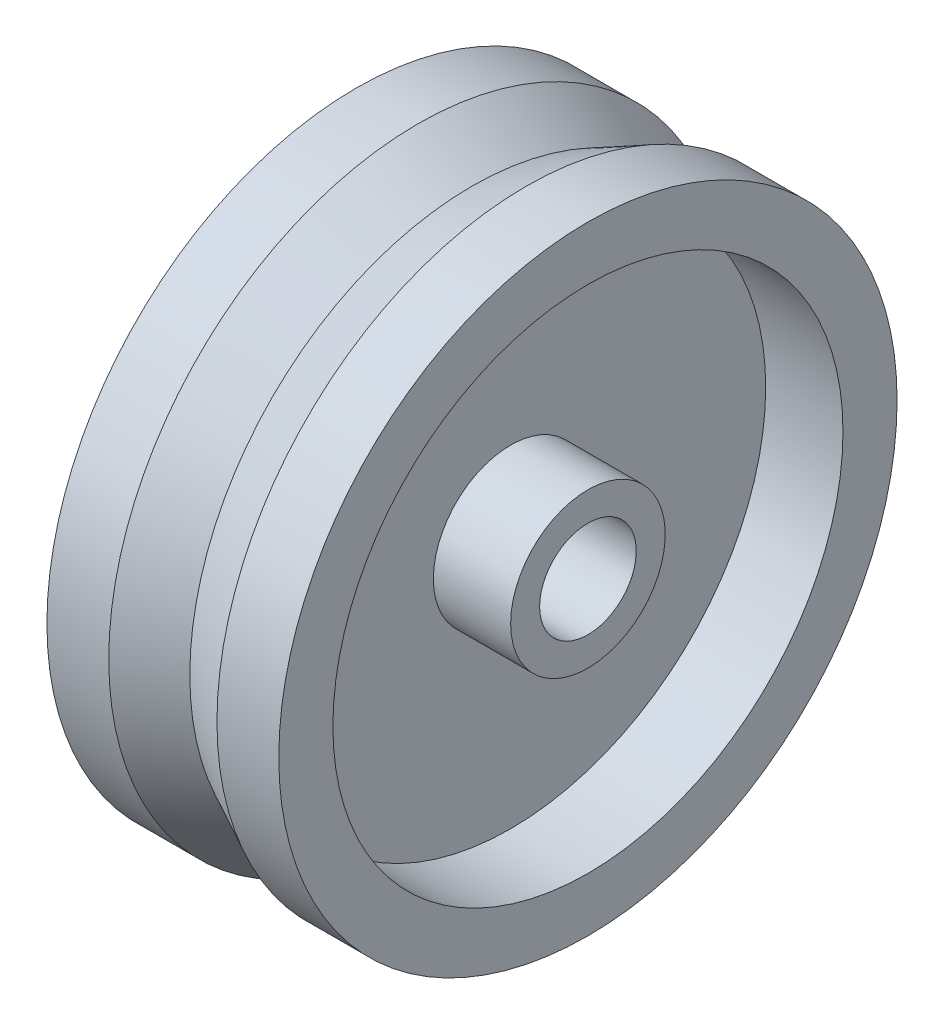
SolidWorks part; units mm, degrees
ref_plane "Ön Düzlem" through (0, 0, 0) normal (0, 0, 1) x (1, 0, 0)
ref_plane "Üst Düzlem" through (0, 0, 0) normal (0, 1, 0) x (1, 0, 0)
ref_plane "Sağ Düzlem" through (0, 0, 0) normal (1, 0, 0) x (0, 0, -1)
sketch "Çizim1" plane through (0, 0, 0) normal (0, 0, 1) x (1, 0, 0)
  line L0 (-5.6086, 3.125) -> (9.3914, 3.125)
  line L1 (9.3914, 3.125) -> (9.3914, 5)
  line L2 (9.3914, 5) -> (4.3914, 5)
  line L3 (4.3914, 5) -> (4.3914, 16.5)
  line L4 (4.3914, 16.5) -> (9.3914, 16.5)
  line L5 (9.3914, 16.5) -> (9.3914, 20)
  line L6 (9.3914, 20) -> (5.3914, 20)
  line L7 (5.3914, 20) -> (1.8914, 18.2566)
  line L8 (1.8914, 18.2566) -> (-1.6086, 20)
  line L9 (-1.6086, 20) -> (-5.6086, 20)
  line L10 (-5.6086, 20) -> (-5.6086, 16.5)
  line L11 (-5.6086, 16.5) -> (-0.6086, 16.5)
  line L12 (-0.6086, 16.5) -> (-0.6086, 5)
  line L13 (-0.6086, 5) -> (-5.6086, 5)
  line L14 (-5.6086, 5) -> (-5.6086, 3.125)
  line L15 (-7.6386, 0) -> (18.0193, 0) construction
  point P18 (1.8914, 3.125)
  dimension "D1" = 6.25
  dimension "D2" = 10
  dimension "D3" = 33
  dimension "D4" = 40
  dimension "D5" = 10
  dimension "D6" = 33
  dimension "D7" = 40
  dimension "D8" = 5
  dimension "D9" = 15
  dimension "D10" = 15
  dimension "D11" = 5
  dimension "D12" = 5
  dimension "D13" = 4
  dimension "D14" = 4
  dimension "D15" = 3.5
revolve "Döndür1" add sketch "Çizim1" angle 360 about L15
